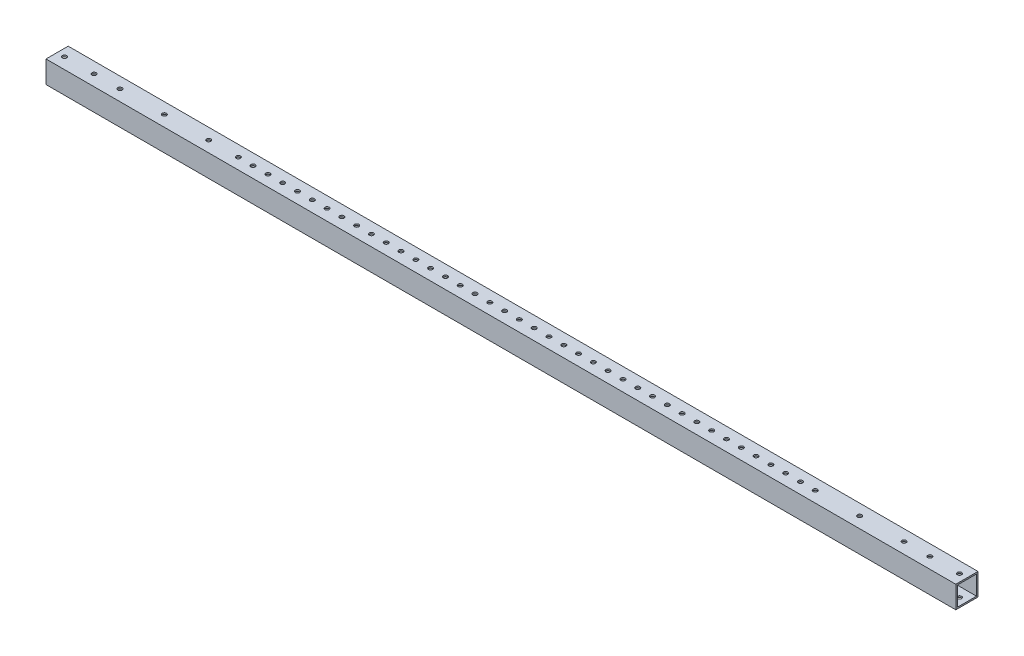
SolidWorks part; units mm, degrees
material "Thornel Mat VMA"
ref_plane "前视基准面" through (0, 0, 0) normal (0, 0, 1) x (1, 0, 0)
ref_plane "上视基准面" through (0, 0, 0) normal (0, 1, 0) x (1, 0, 0)
ref_plane "右视基准面" through (0, 0, 0) normal (1, 0, 0) x (0, 0, -1)
other "Configuration Table"
sketch "草图1" plane through (0, 0, 0) normal (0, 1, 0) x (1, 0, 0)
  line L0 (0, 0) -> (-615, 0)
  dimension "D1" = 615
other "铝管 15X15X1(1)"
ref_plane "基准面1" through (0, 0, 0) normal (-1, 0, 0) x (0, 0, 1)
sketch "草图11" plane through (0, 0, 0) normal (-1, 0, 0) x (0, 0, 1)
  line L1 (-7.5, -7.5) -> (7.5, -7.5)
  line L2 (-7.5, -7.5) -> (-7.5, 7.5)
  line L3 (-7.5, 7.5) -> (7.5, 7.5)
  line L4 (7.5, -7.5) -> (7.5, 7.5)
  line L5 (-7.5, -7.5) -> (7.5, 7.5) construction
  line L6 (-7.5, 7.5) -> (7.5, -7.5) construction
  line L7 (-6.5, -6.5) -> (6.5, -6.5)
  line L8 (-6.5, -6.5) -> (-6.5, 6.5)
  line L9 (-6.5, 6.5) -> (6.5, 6.5)
  line L10 (6.5, -6.5) -> (6.5, 6.5)
  line L11 (-6.5, -6.5) -> (6.5, 6.5) construction
  line L12 (-6.5, 6.5) -> (6.5, -6.5) construction
  point P0 (0, 0)
  point P6 (0, 0)
  point P11 (0, 0)
  dimension "D1" = 15
  dimension "D2" = 15
  dimension "D3" = 13
  dimension "D4" = 13
sketch "草图12" plane through (0, 7.5, 0) normal (0, 1, 0) x (1, 0, 0)
  line L0 (0, -7.5) -> (0, 7.5) construction
  line L3 (0, 0) -> (-615, 0) construction
  line L4 (-615, -7.5) -> (-615, 7.5) construction
  circle A0 centre (-610, 0) radius 1.45
  circle A1 centre (-590, 0) radius 1.45
  circle A2 centre (-25, 0) radius 1.45
  circle A3 centre (-5, 0) radius 1.45
  dimension "D1" = 2.9
  dimension "D2" = 2.9
  dimension "D4" = 20
  dimension "D5" = 2.9
  dimension "D6" = 5
  dimension "D7" = 20
  dimension "D8" = 2.9
  dimension "D3" = 5
extrude "切除-拉伸1" cut sketch "草图12" against normal through all
sketch "草图13" plane through (0, -7.5, 0) normal (0, -1, 0) x (1, 0, 0)
  line L0 (-72.5, -7.5) -> (-72.5, 7.5) construction
  line L1 (-615, -7.5) -> (0, -7.5) construction
  line L2 (-615, 7.5) -> (0, 7.5) construction
  line L3 (0, 0) -> (-615, 0) construction
  line L5 (-542.5, -7.5) -> (-542.5, 7.5) construction
  line L7 (0, -7.5) -> (0, 7.5) construction
  line L8 (-615, -7.5) -> (-615, 7.5) construction
  circle A0 centre (-102.5, 0) radius 1.45
  circle A1 centre (-72.5, 0) radius 1.45
  circle A2 centre (-42.5, 0) radius 1.45
  circle A3 centre (-542.5, 0) radius 1.45
  circle A4 centre (-512.5, 0) radius 1.45
  circle A5 centre (-572.5, 0) radius 1.45
  dimension "D1" = 2.9
  dimension "D2" = 2.9
  dimension "D3" = 30
  dimension "D5" = 2.9
  dimension "D6" = 2.9
  dimension "D4" = 72.5
  dimension "D7" = 30
  dimension "D8" = 72.5
extrude "切除-拉伸2" cut sketch "草图13" against normal through all
sketch "草图14" plane through (0, -7.5, 0) normal (0, -1, 0) x (1, 0, 0)
  line L0 (0, 0) -> (-615, 0) construction
  circle A0 centre (-492.5, 0) radius 1.45
  circle A1 centre (-512.5, 0) radius 1.45 construction
  circle A2 centre (-482.5, 0) radius 1.45
  circle A3 centre (-472.5, 0) radius 1.45
  circle A4 centre (-462.5, 0) radius 1.45
  circle A5 centre (-452.5, 0) radius 1.45
  circle A6 centre (-442.5, 0) radius 1.45
  circle A7 centre (-432.5, 0) radius 1.45
  circle A8 centre (-422.5, 0) radius 1.45
  circle A9 centre (-412.5, 0) radius 1.45
  circle A10 centre (-402.5, 0) radius 1.45
  circle A11 centre (-392.5, 0) radius 1.45
  circle A12 centre (-382.5, 0) radius 1.45
  circle A13 centre (-372.5, 0) radius 1.45
  circle A14 centre (-362.5, 0) radius 1.45
  circle A15 centre (-352.5, 0) radius 1.45
  circle A16 centre (-342.5, 0) radius 1.45
  circle A17 centre (-332.5, 0) radius 1.45
  circle A18 centre (-322.5, 0) radius 1.45
  circle A19 centre (-312.5, 0) radius 1.45
  circle A20 centre (-302.5, 0) radius 1.45
  circle A21 centre (-292.5, 0) radius 1.45
  circle A22 centre (-282.5, 0) radius 1.45
  circle A23 centre (-272.5, 0) radius 1.45
  circle A24 centre (-262.5, 0) radius 1.45
  circle A25 centre (-252.5, 0) radius 1.45
  circle A26 centre (-242.5, 0) radius 1.45
  circle A27 centre (-232.5, 0) radius 1.45
  circle A28 centre (-222.5, 0) radius 1.45
  circle A29 centre (-212.5, 0) radius 1.45
  circle A30 centre (-202.5, 0) radius 1.45
  circle A31 centre (-192.5, 0) radius 1.45
  circle A32 centre (-182.5, 0) radius 1.45
  circle A33 centre (-172.5, 0) radius 1.45
  circle A34 centre (-162.5, 0) radius 1.45
  circle A35 centre (-152.5, 0) radius 1.45
  circle A36 centre (-142.5, 0) radius 1.45
  circle A37 centre (-132.5, 0) radius 1.45
  circle A38 centre (-122.5, 0) radius 1.45
  circle A39 centre (-112.5, 0) radius 1.45
  circle A46 centre (-72.5, 0) radius 1.45 [skipped]
  circle A47 centre (-62.5, 0) radius 1.45 [skipped]
  circle A48 centre (-52.5, 0) radius 1.45 [skipped]
  circle A50 centre (-102.5, 0) radius 1.45 [skipped]
  circle A51 centre (-92.5, 0) radius 1.45 [skipped]
  circle A52 centre (-82.5, 0) radius 1.45 [skipped]
  dimension "D1" = 2.9
  dimension "D2" = 20
  dimension "D3" = 45
extrude "切除-拉伸3" cut sketch "草图14" against normal through all
